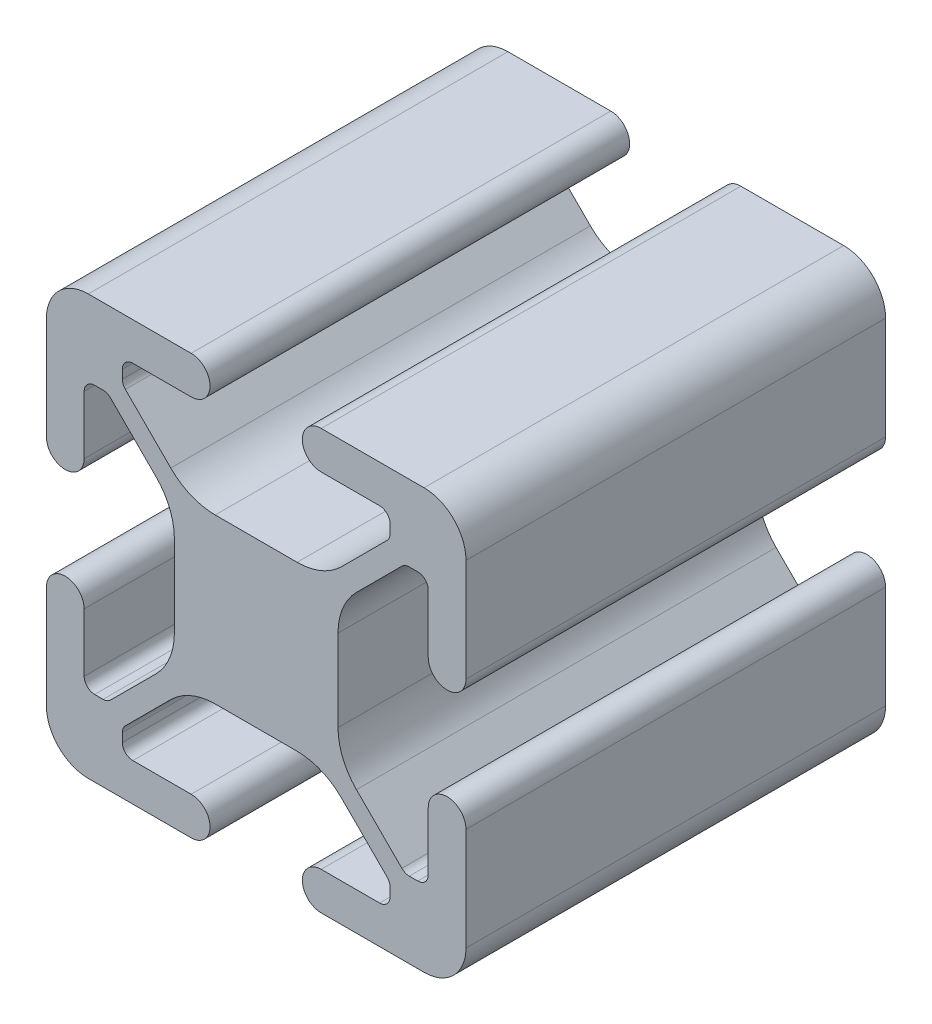
SolidWorks part; units mm, degrees
ref_plane "前视基准面" through (0, 0, 0) normal (0, 0, 1) x (1, 0, 0)
ref_plane "上视基准面" through (0, 0, 0) normal (0, 1, 0) x (1, 0, 0)
ref_plane "右视基准面" through (0, 0, 0) normal (1, 0, 0) x (0, 0, -1)
sketch "草图2" plane through (0, 0, 0) normal (0, 0, 1) x (1, 0, 0)
  line L0 (-1.0428, -10.0859) -> (3.8572, -10.0859)
  line L1 (1.0762, -11.8859) -> (3.8572, -11.8859)
  line L2 (2.8854, -15.3072) -> (0.7226, -13.1443)
  line L3 (2.1786, -16.0141) -> (0.0157, -13.8512)
  line L4 (-3.0428, -12.0859) -> (-3.0428, -16.9859)
  line L5 (-1.2428, -14.2048) -> (-1.2428, -16.9859)
  line L6 (-0.7428, -13.7048) -> (-0.3378, -13.7048)
  line L7 (0.5762, -12.3859) -> (0.5762, -12.7908)
  line L8 (-1.0428, -30.0859) -> (3.8572, -30.0859)
  line L9 (1.0762, -28.2859) -> (3.8572, -28.2859)
  line L10 (2.8854, -24.8645) -> (0.7226, -27.0274)
  line L11 (2.1786, -24.1577) -> (0.0157, -26.3205)
  line L12 (-3.0428, -28.0859) -> (-3.0428, -23.1859)
  line L13 (-1.2428, -25.9669) -> (-1.2428, -23.1859)
  line L14 (-0.7428, -26.4669) -> (-0.3378, -26.4669)
  line L15 (0.5762, -27.7859) -> (0.5762, -27.3809)
  line L16 (14.9572, -10.0859) -> (10.0572, -10.0859)
  line L17 (12.8383, -11.8859) -> (10.0572, -11.8859)
  line L18 (11.029, -15.3072) -> (13.1919, -13.1443)
  line L19 (11.7359, -16.0141) -> (13.8988, -13.8512)
  line L20 (16.9572, -12.0859) -> (16.9572, -16.9859)
  line L21 (15.1572, -14.2048) -> (15.1572, -16.9859)
  line L22 (14.6572, -13.7048) -> (14.2523, -13.7048)
  line L23 (13.3383, -12.3859) -> (13.3383, -12.7908)
  line L24 (14.9572, -30.0859) -> (10.0572, -30.0859)
  line L25 (12.8383, -28.2859) -> (10.0572, -28.2859)
  line L26 (11.029, -24.8645) -> (13.1919, -27.0274)
  line L27 (11.7359, -24.1577) -> (13.8988, -26.3205)
  line L28 (16.9572, -28.0859) -> (16.9572, -23.1859)
  line L29 (15.1572, -25.9669) -> (15.1572, -23.1859)
  line L30 (14.6572, -26.4669) -> (14.2523, -26.4669)
  line L31 (13.3383, -27.7859) -> (13.3383, -27.3809)
  line L32 (5.0068, -16.1859) -> (8.9077, -16.1859)
  line L33 (10.8572, -18.1354) -> (10.8572, -22.0363)
  line L34 (3.0572, -18.1354) -> (3.0572, -22.0363)
  line L35 (5.0068, -23.9859) -> (8.9077, -23.9859)
  circle A0 centre (6.9572, -20.0859) radius 2.5
  arc A1 (2.8854, -15.3072) -> (5.0068, -16.1859) centre (5.0068, -13.1859) ccw
  arc A2 (3.0572, -18.1354) -> (2.1786, -16.0141) centre (0.0572, -18.1354) ccw
  arc A3 (3.8572, -11.8859) -> (3.8572, -10.0859) centre (3.8572, -10.9859) ccw
  arc A4 (0.5762, -12.7908) -> (0.7226, -13.1443) centre (1.0762, -12.7908) ccw
  arc A5 (0.0157, -13.8512) -> (-0.3378, -13.7048) centre (-0.3378, -14.2048) ccw
  arc A6 (-3.0428, -16.9859) -> (-1.2428, -16.9859) centre (-2.1428, -16.9859) ccw
  arc A7 (-1.0428, -10.0859) -> (-3.0428, -12.0859) centre (-1.0428, -12.0859) ccw
  arc A8 (-0.7428, -13.7048) -> (-1.2428, -14.2048) centre (-0.7428, -14.2048) ccw
  arc A9 (1.0762, -11.8859) -> (0.5762, -12.3859) centre (1.0762, -12.3859) ccw
  arc A10 (5.0068, -23.9859) -> (2.8854, -24.8645) centre (5.0068, -26.9859) ccw
  arc A11 (2.1786, -24.1577) -> (3.0572, -22.0363) centre (0.0572, -22.0363) ccw
  arc A12 (3.8572, -30.0859) -> (3.8572, -28.2859) centre (3.8572, -29.1859) ccw
  arc A13 (0.7226, -27.0274) -> (0.5762, -27.3809) centre (1.0762, -27.3809) ccw
  arc A14 (-0.3378, -26.4669) -> (0.0157, -26.3205) centre (-0.3378, -25.9669) ccw
  arc A15 (-1.2428, -23.1859) -> (-3.0428, -23.1859) centre (-2.1428, -23.1859) ccw
  arc A16 (-3.0428, -28.0859) -> (-1.0428, -30.0859) centre (-1.0428, -28.0859) ccw
  arc A17 (-1.2428, -25.9669) -> (-0.7428, -26.4669) centre (-0.7428, -25.9669) ccw
  arc A18 (0.5762, -27.7859) -> (1.0762, -28.2859) centre (1.0762, -27.7859) ccw
  arc A19 (8.9077, -16.1859) -> (11.029, -15.3072) centre (8.9077, -13.1859) ccw
  arc A20 (11.7359, -16.0141) -> (10.8572, -18.1354) centre (13.8572, -18.1354) ccw
  arc A21 (10.0572, -10.0859) -> (10.0572, -11.8859) centre (10.0572, -10.9859) ccw
  arc A22 (13.1919, -13.1443) -> (13.3383, -12.7908) centre (12.8383, -12.7908) ccw
  arc A23 (14.2523, -13.7048) -> (13.8988, -13.8512) centre (14.2523, -14.2048) ccw
  arc A24 (15.1572, -16.9859) -> (16.9572, -16.9859) centre (16.0572, -16.9859) ccw
  arc A25 (16.9572, -12.0859) -> (14.9572, -10.0859) centre (14.9572, -12.0859) ccw
  arc A26 (15.1572, -14.2048) -> (14.6572, -13.7048) centre (14.6572, -14.2048) ccw
  arc A27 (13.3383, -12.3859) -> (12.8383, -11.8859) centre (12.8383, -12.3859) ccw
  arc A28 (11.029, -24.8645) -> (8.9077, -23.9859) centre (8.9077, -26.9859) ccw
  arc A29 (10.8572, -22.0363) -> (11.7359, -24.1577) centre (13.8572, -22.0363) ccw
  arc A30 (10.0572, -28.2859) -> (10.0572, -30.0859) centre (10.0572, -29.1859) ccw
  arc A31 (13.3383, -27.3809) -> (13.1919, -27.0274) centre (12.8383, -27.3809) ccw
  arc A32 (13.8988, -26.3205) -> (14.2523, -26.4669) centre (14.2523, -25.9669) ccw
  arc A33 (16.9572, -23.1859) -> (15.1572, -23.1859) centre (16.0572, -23.1859) ccw
  arc A34 (14.9572, -30.0859) -> (16.9572, -28.0859) centre (14.9572, -28.0859) ccw
  arc A35 (14.6572, -26.4669) -> (15.1572, -25.9669) centre (14.6572, -25.9669) ccw
  arc A36 (12.8383, -28.2859) -> (13.3383, -27.7859) centre (12.8383, -27.7859) ccw
extrude "凸台-拉伸1" add sketch "草图2" along normal blind 20 contours L0 A3 L1 A9 L7 A4 L2 A1 L32 A19 L18 A22 L23 A27 L17 A21 L16 A25 L20 A24 L21 A26 L22 A23 L19 A20 L33 A29 L27 A32 L30 A35 L29 A33 L28 A34 L24 A30 L25 A36 L31 A31 L26 A28 L35 A10 L10 A13 L15 A18 L9 A12 L8 A16 L12 A15 L13 A17 L14 A14 L11 A11 L34 A2 L3 A5 L6 A8 L5 A6 L4 A7
